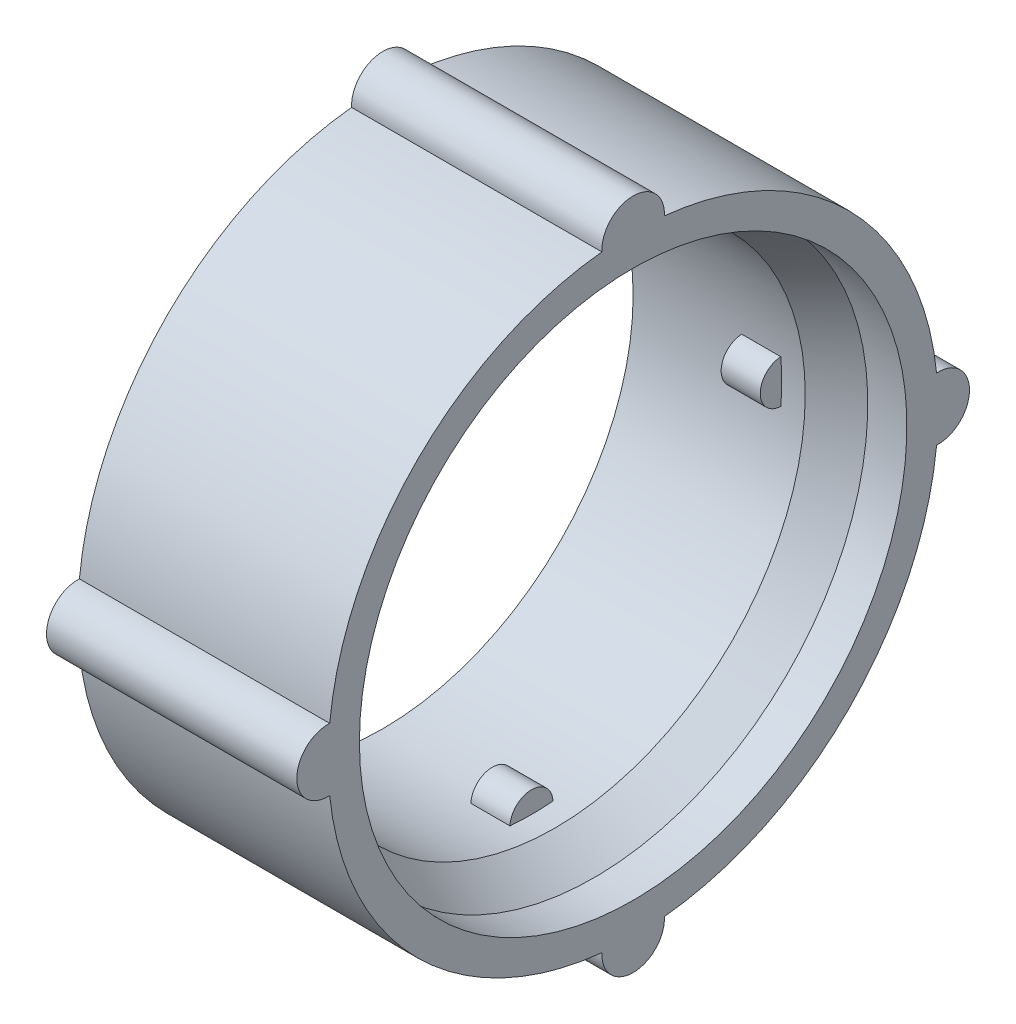
SolidWorks part; units mm, degrees
ref_plane "Front Plane" through (0, 0, 0) normal (0, 0, 1) x (1, 0, 0)
ref_plane "Top Plane" through (0, 0, 0) normal (0, 1, 0) x (1, 0, 0)
ref_plane "Right Plane" through (0, 0, 0) normal (1, 0, 0) x (0, 0, -1)
sketch "Sketch1" plane through (0, 0, 0) normal (0, 1, 0) x (1, 0, 0)
  line L0 (0, 0) -> (16, 0) construction
  line L1 (0, 16) -> (16, 16)
  line L2 (0, 16) -> (0, 0) construction
  line L3 (16, 16) -> (16, 0) construction
  line L4 (0, 19.5) -> (16, 19.5)
  line L5 (0, 19.5) -> (0, 16)
  line L6 (16, 19.5) -> (16, 16)
  dimension "D1" = 16
  dimension "D2" = 16
  dimension "D3" = 3.5
revolve "Revolve1" add sketch "Sketch1" angle 360 about L0
sketch "Sketch2" plane through (0, 0, 0) normal (0, 1, 0) x (1, 0, 0)
  line L0 (16, 17.5) -> (13.5, 17.5)
  line L1 (16, -19.5) -> (16, 19.5) construction
  line L2 (13.5, 17.5) -> (11, 16)
  line L3 (16, 16) -> (0, 16) construction
  line L4 (11, 16) -> (16, 16)
  line L5 (16, 16) -> (16, 17.5)
  line L6 (0, 0) -> (18.5824, 0) construction
  dimension "D1" = 2.5
  dimension "D2" = 2.5
  dimension "D3" = 17.5
revolve "Cut-Revolve1" cut sketch "Sketch2" angle 360 about L6
sketch "Sketch3" plane through (0, 0, 0) normal (-1, 0, 0) x (0, 0, 1)
  circle A0 centre (0, 16) radius 1.375
  circle A1 centre (0, 0) radius 16 construction
  circle A3 centre (16, 0) radius 1.375
  circle A4 centre (0, -16) radius 1.375
  circle A5 centre (-16, 0) radius 1.375
  point P13 (0, 0)
  dimension "D2" = 2.75
  dimension "D1" = 4
extrude "Boss-Extrude1" add sketch "Sketch3" against normal blind 2.5 from offset 7 offset against normal yes
sketch "Sketch4" plane through (0, 0, 0) normal (-1, 0, 0) x (0, 0, 1)
  circle A0 centre (0, 19.5) radius 2
  circle A1 centre (0, 0) radius 19.5 construction
  circle A2 centre (19.5, 0) radius 2
  circle A3 centre (0, -19.5) radius 2
  circle A4 centre (-19.5, 0) radius 2
  point P13 (0, 0)
  dimension "D1" = 4
  dimension "D2" = 4
extrude "Boss-Extrude2" add sketch "Sketch4" against normal up to surface (16 mm away) up to face at (16, 0, 19.5)
